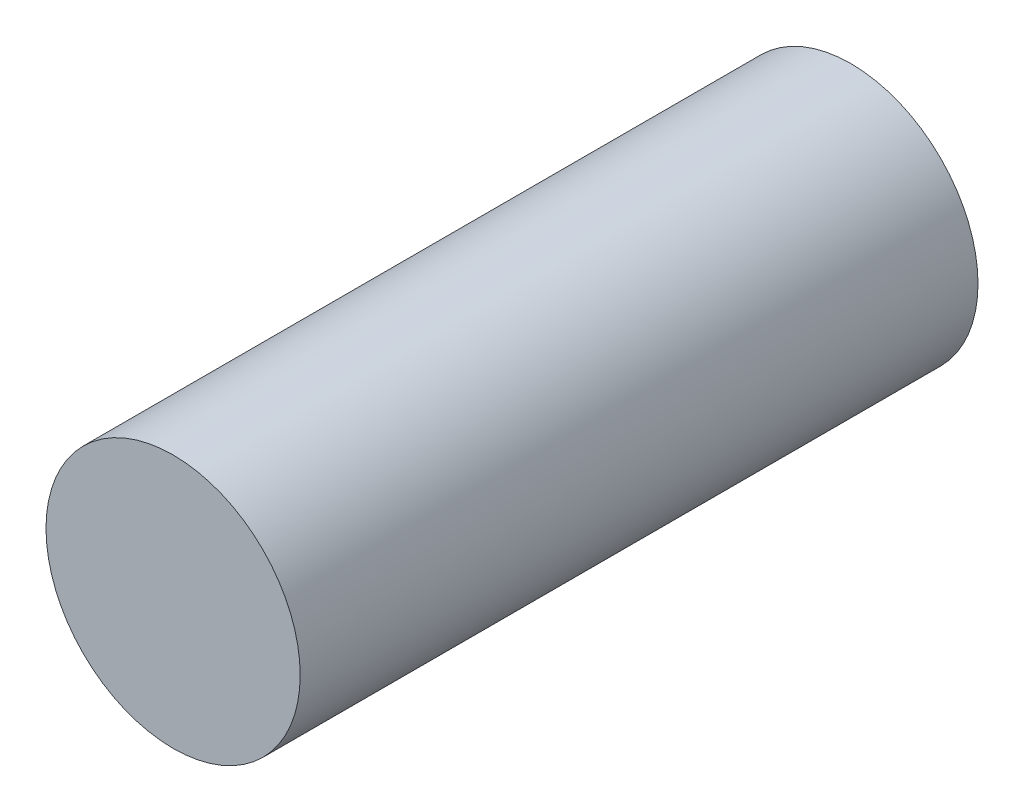
SolidWorks part; units mm, degrees
material "Plain Carbon Steel"
ref_plane "Front" through (0, 0, 0) normal (0, 0, 1) x (1, 0, 0)
ref_plane "Top" through (0, 0, 0) normal (0, 1, 0) x (1, 0, 0)
ref_plane "Right" through (0, 0, 0) normal (1, 0, 0) x (0, 0, -1)
sketch "Sketch2" plane through (0, 0, 0) normal (0, 0, 1) x (1, 0, 0)
  circle A0 centre (0, 0) radius 2.3813
  dimension "D1" = 4.7625
extrude "Boss-Extrude1" add sketch "Sketch2" along normal mid plane 12.7
